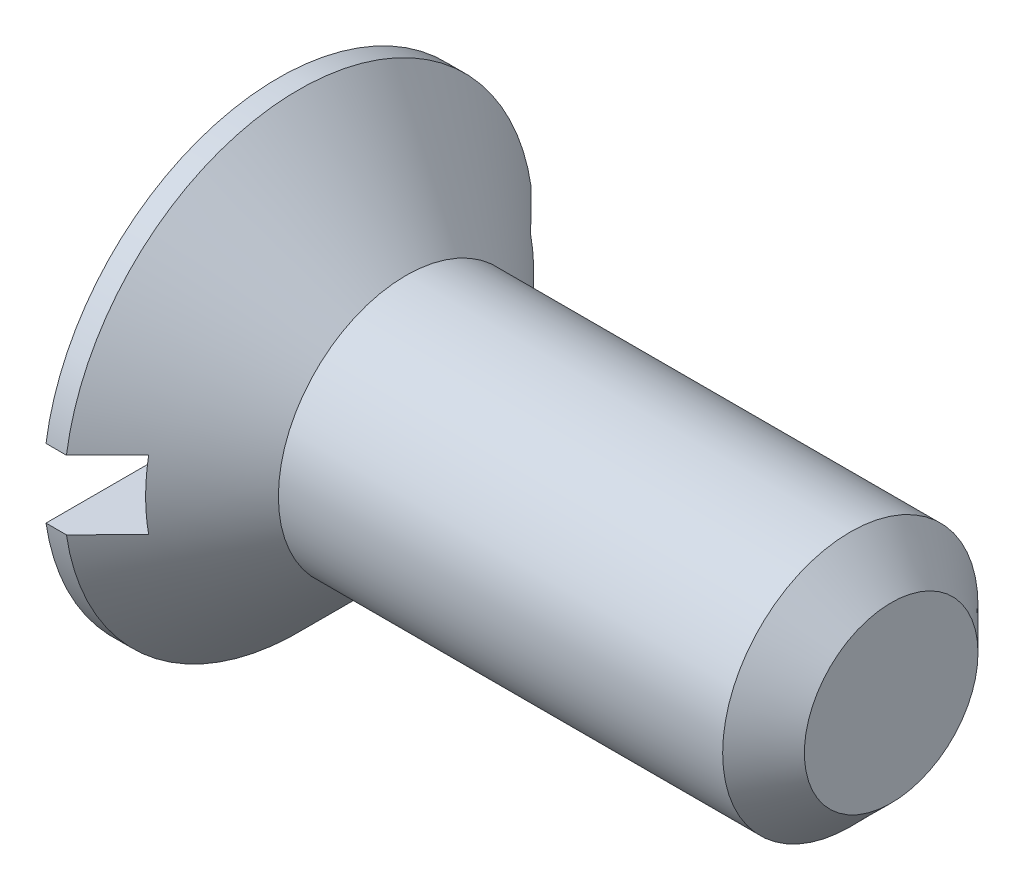
SolidWorks part; units mm, degrees
ref_plane "PL_ВЫРАВ" through (0, 0, 0) normal (0, 0, 1) x (1, 0, 0)
ref_plane "СВЕРХУ" through (0, 0, 0) normal (0, 1, 0) x (1, 0, 0)
ref_plane "СПРАВА" through (0, 0, 0) normal (1, 0, 0) x (0, 0, -1)
sketch "Эскиз1" plane through (0, 0, 0) normal (1, 0, 0) x (0, 0, -1)
  circle A0 centre (0, 0) radius 2.5
  dimension "d" = 5
extrude "Основание-Вытянуть" add sketch "Эскиз1" along normal blind 12
cosmetic thread "Условное изображение резьбы1"
chamfer "Фаска1" distance 0.8 angle 45 1 edges at (12, 0, -2.5)
revolve "Бобышка-Повернуть1" add sketch "Эскиз2" angle 360 about L2
sketch "Эскиз2" plane through (0, 0, 0) normal (0, 0, 1) x (1, 0, 0)
  line L1 (0, 4.6) -> (0.4, 4.6)
  line L2 (0, 0) -> (33.6444, 0) construction
  line L3 (11.2, 0) -> (0, 0) construction
  line L4 (0.4, 4.6) -> (2.5, 2.5)
  line L5 (0, 0) -> (0, 4.6)
  line L6 (0, 2.5) -> (0, -2.5) construction
  line L7 (2.5, 2.5) -> (2.5, 0)
  line L8 (0, 0) -> (2.5, 0)
  line L9 (11.2, 2.5) -> (0, 2.5) construction
  dimension "K" = 2.5
  dimension "D3" = 45
  dimension "D" = 9.2
sketch "Эскиз4" plane through (0, 0, 0) normal (0, 0, 1) x (1, 0, 0)
  line L0 (0, 0.675) -> (1.2, 0.675)
  line L1 (1.2, 0.675) -> (1.2, -0.675)
  line L2 (1.2, -0.675) -> (0, -0.675)
  line L4 (-29.8265, 0) -> (40, 0) construction
  line L5 (11.2, 0) -> (2.5, 0) construction
  line L6 (0, 0.675) -> (0, -0.675)
  line L7 (0, 4.6) -> (0, -4.6) construction
  dimension "Ширина" = 1.35
  dimension "Глубина" = 1.2
extrude "Вырез-Вытянуть1" cut sketch "Эскиз4" against normal through all and the other way through all
